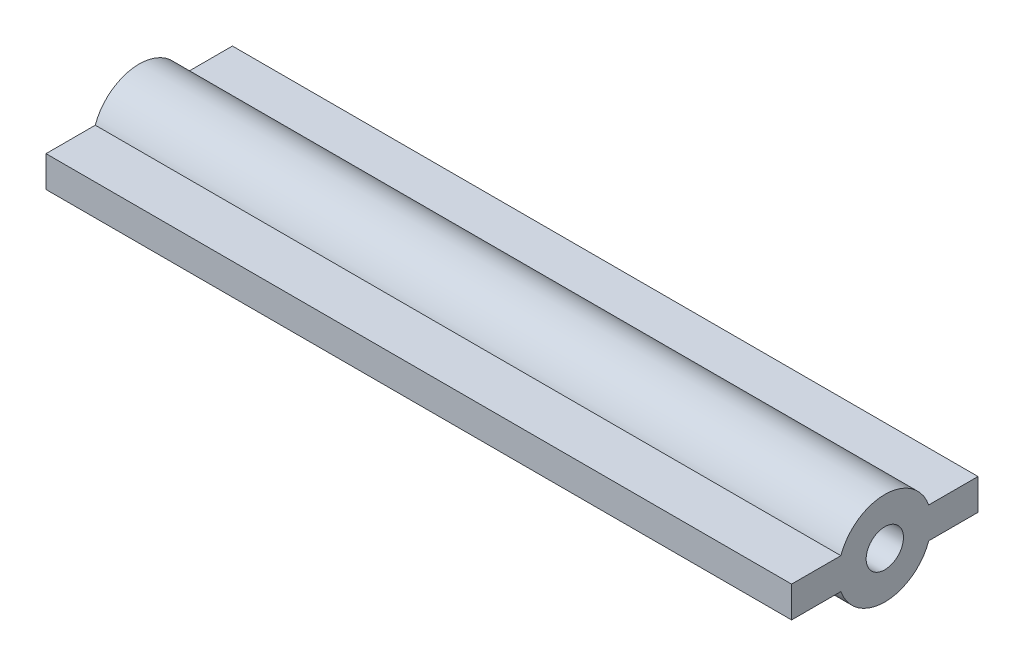
SolidWorks part; units mm, degrees
ref_plane "Спереди" through (0, 0, 0) normal (0, 0, 1) x (1, 0, 0)
ref_plane "Сверху" through (0, 0, 0) normal (0, 1, 0) x (1, 0, 0)
ref_plane "Справа" through (0, 0, 0) normal (1, 0, 0) x (0, 0, -1)
sketch "Эскиз1" plane through (0, 0, 0) normal (1, 0, 0) x (0, 0, -1)
  line L0 (-15, 0) -> (0, 0) construction
  line L1 (-15, 2.5) -> (-7.0711, 2.5)
  line L2 (-15, 2.5) -> (-15, -2.5)
  line L3 (-15, -2.5) -> (-7.0711, -2.5)
  line L4 (15, 2.5) -> (15, -2.5)
  line L5 (0, 0) -> (15, 0) construction
  line L6 (7.0711, 2.5) -> (15, 2.5)
  line L7 (7.0711, -2.5) -> (15, -2.5)
  arc A0 (-7.0711, -2.5) -> (7.0711, -2.5) centre (0, 0) ccw
  arc A1 (7.0711, 2.5) -> (-7.0711, 2.5) centre (0, 0) ccw
  circle A2 centre (0, 0) radius 3
  dimension "D3" = 15
  dimension "D4" = 6
  dimension "D1" = 5
  dimension "D2" = 30
extrude "Бобышка-Вытянуть1" add sketch "Эскиз1" along normal blind 120
sketch "Эскиз2" plane through (0, 0, 0) normal (-1, 0, 0) x (0, 0, 1)
  line L0 (1.6889, 3.6716) -> (4.0242, 0.3732)
  line L1 (4.0242, 0.3732) -> (2.3353, -3.2985)
  line L2 (2.3353, -3.2985) -> (-1.6889, -3.6716)
  line L3 (-1.6889, -3.6716) -> (-4.0242, -0.3732)
  line L4 (-4.0242, -0.3732) -> (-2.3353, 3.2985)
  line L5 (-2.3353, 3.2985) -> (1.6889, 3.6716)
  circle A0 centre (0, 0) radius 4.0415 construction
  dimension "D1" = 7
extrude "Вырез-Вытянуть1" cut sketch "Эскиз2" against normal blind 6
